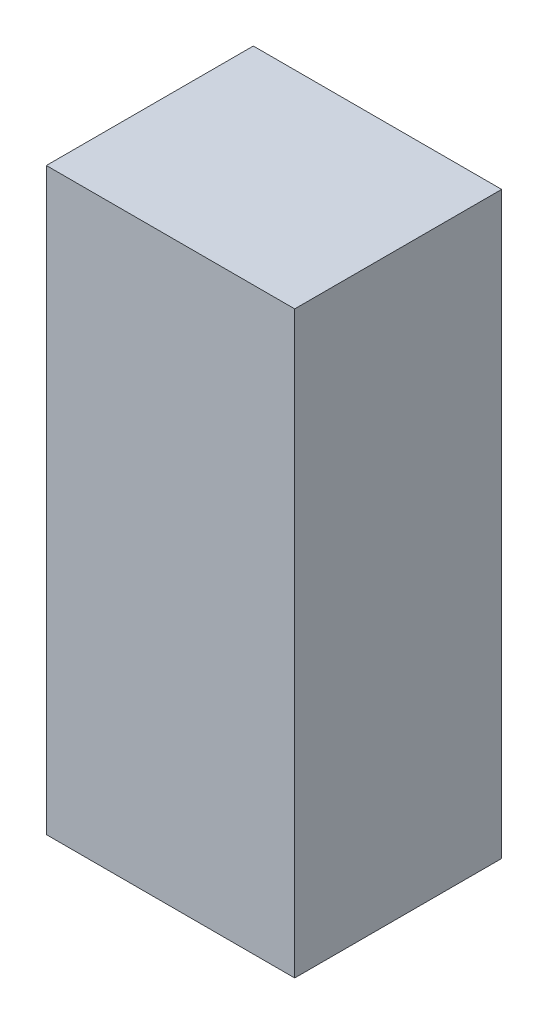
SolidWorks part; units mm, degrees
ref_plane "Front Plane" through (0, 0, 0) normal (0, 0, 1) x (1, 0, 0)
ref_plane "Top Plane" through (0, 0, 0) normal (0, 1, 0) x (1, 0, 0)
ref_plane "Right Plane" through (0, 0, 0) normal (1, 0, 0) x (0, 0, -1)
sketch "Sketch1" plane through (0, 0, 0) normal (0, 0, 1) x (1, 0, 0)
  line L1 (-6, 14) -> (6, 14)
  line L2 (-6, 14) -> (-6, -14)
  line L3 (-6, -14) -> (6, -14)
  line L4 (6, 14) -> (6, -14)
  line L5 (-6, 14) -> (6, -14) construction
  line L6 (-6, -14) -> (6, 14) construction
  point P0 (0, 0)
extrude "Boss-Extrude1" add sketch "Sketch1" against normal blind 10
